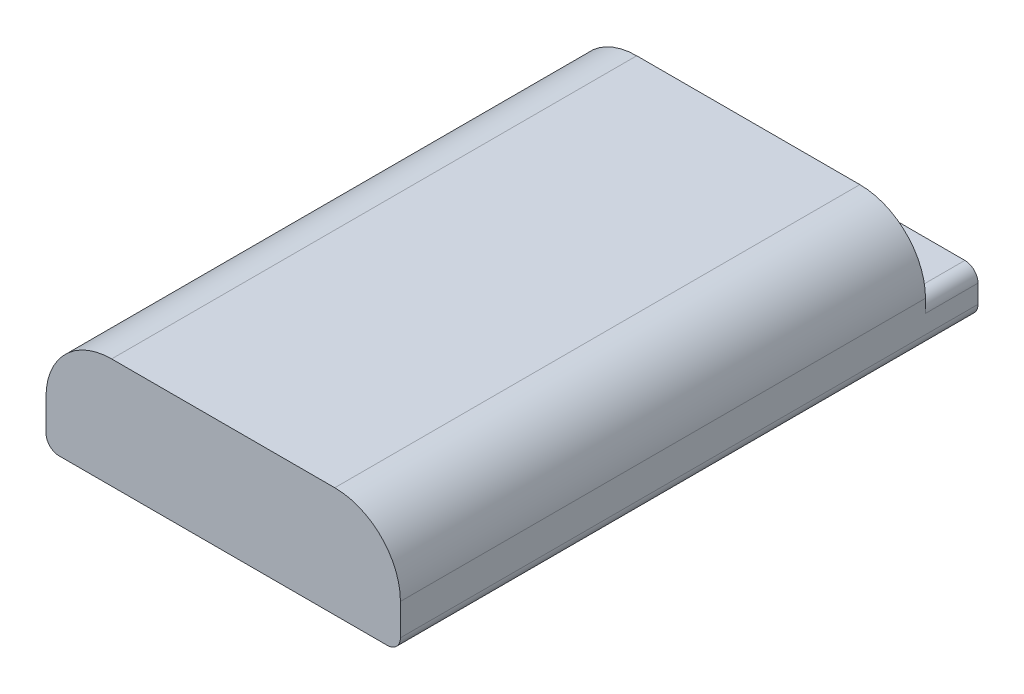
SolidWorks part; units mm, degrees
ref_plane "Front Plane" through (0, 0, 0) normal (0, 0, 1) x (1, 0, 0)
ref_plane "Top Plane" through (0, 0, 0) normal (0, 1, 0) x (1, 0, 0)
ref_plane "Right Plane" through (0, 0, 0) normal (1, 0, 0) x (0, 0, -1)
sketch "Sketch1" plane through (0, 0, 0) normal (0, 1, 0) x (1, 0, 0)
  line L1 (-17.145, 27.94) -> (17.145, 27.94)
  line L2 (-17.145, 27.94) -> (-17.145, -27.94)
  line L3 (-17.145, -27.94) -> (17.145, -27.94)
  line L4 (17.145, 27.94) -> (17.145, -27.94)
  line L5 (-17.145, 27.94) -> (17.145, -27.94) construction
  line L6 (-17.145, -27.94) -> (17.145, 27.94) construction
  point P0 (0, 0)
  dimension "D1" = 55.88
  dimension "D2" = 34.29
extrude "Boss-Extrude1" add sketch "Sketch1" along normal blind 4.318
sketch "Sketch2" plane through (0, 4.318, 0) normal (0, 1, 0) x (1, 0, 0)
  line L0 (17.145, -27.94) -> (17.145, 27.94) construction
  line L1 (-17.145, -27.94) -> (17.145, -27.94)
  line L2 (-17.145, -27.94) -> (-17.145, 22.86)
  line L3 (-17.145, 22.86) -> (17.145, 22.86)
  line L4 (17.145, -27.94) -> (17.145, 22.86)
  dimension "D1" = 50.8
extrude "Boss-Extrude2" add sketch "Sketch2" along normal blind 6.35
sketch "Sketch3" plane through (0, 0, -27.94) normal (0, 0, -1) x (-1, 0, 0)
  line L4 (-17.145, 0) -> (17.145, 0)
  line L5 (17.145, 0) -> (17.145, 4.318)
  line L6 (17.145, 4.318) -> (-17.145, 4.318)
  line L7 (-17.145, 4.318) -> (-17.145, 0)
  line L8 (-15.875, 0) -> (15.875, 0)
  line L9 (17.145, 1.27) -> (17.145, 3.048)
  line L10 (15.875, 4.318) -> (-15.875, 4.318)
  line L11 (-17.145, 3.048) -> (-17.145, 1.27)
  arc A0 (17.145, 3.048) -> (15.875, 4.318) centre (15.875, 3.048) ccw
  arc A1 (15.875, 0) -> (17.145, 1.27) centre (15.875, 1.27) ccw
  arc A2 (-15.875, 0) -> (-17.145, 1.27) centre (-15.875, 1.27) cw
  arc A3 (-15.875, 4.318) -> (-17.145, 3.048) centre (-15.875, 3.048) ccw
  dimension "D2" = 1.27
  dimension "D1" = 0
extrude "Cut-Extrude1" cut sketch "Sketch3" against normal up to surface (5.08 mm away) flip side to cut up to face at (0, 7.493, -22.86)
sketch "Sketch4" plane through (0, 0, -22.86) normal (0, 0, -1) x (-1, 0, 0)
  line L0 (15.875, 0) -> (17.145, 0) construction
  line L1 (17.145, 0) -> (17.145, 1.27) construction
  line L2 (-17.145, 0) -> (-15.875, 0) construction
  line L3 (-17.145, 1.27) -> (-17.145, 0) construction
  line L4 (-17.145, 10.668) -> (-17.145, 3.048) construction
  line L5 (-15.875, 4.318) -> (15.875, 4.318) construction
  line L6 (17.145, 3.048) -> (17.145, 10.668) construction
  line L7 (17.145, 10.668) -> (-17.145, 10.668) construction
  line L8 (15.875, 0) -> (17.145, 0)
  line L9 (17.145, 0) -> (17.145, 1.27)
  line L10 (-17.145, 0) -> (-15.875, 0)
  line L11 (-17.145, 1.27) -> (-17.145, 0)
  line L12 (-17.145, 4.318) -> (-17.145, 3.048)
  line L13 (-15.875, 4.318) -> (15.875, 4.318)
  line L14 (17.145, 3.048) -> (17.145, 4.318)
  line L15 (10.795, 10.668) -> (-10.795, 10.668)
  arc A0 (15.875, 0) -> (17.145, 1.27) centre (15.875, 1.27) ccw construction
  arc A1 (-17.145, 1.27) -> (-15.875, 0) centre (-15.875, 1.27) ccw construction
  arc A2 (-15.875, 4.318) -> (-17.145, 3.048) centre (-15.875, 3.048) ccw construction
  arc A3 (17.145, 3.048) -> (15.875, 4.318) centre (15.875, 3.048) ccw construction
  arc A4 (15.875, 0) -> (17.145, 1.27) centre (15.875, 1.27) ccw
  arc A5 (-17.145, 1.27) -> (-15.875, 0) centre (-15.875, 1.27) ccw
  arc A6 (-15.875, 4.318) -> (-17.145, 3.048) centre (-15.875, 3.048) ccw
  arc A7 (17.145, 3.048) -> (15.875, 4.318) centre (15.875, 3.048) ccw
  arc A8 (17.145, 4.318) -> (10.795, 10.668) centre (10.795, 4.318) ccw
  arc A9 (-17.145, 4.318) -> (-10.795, 10.668) centre (-10.795, 4.318) cw
  line M7 (-17.145, 10.668) -> (-17.145, 3.048)
  line M11 (17.145, 3.048) -> (17.145, 10.668)
  line M12 (17.145, 10.668) -> (-17.145, 10.668)
  dimension "D1" = 6.35
extrude "Cut-Extrude2" cut sketch "Sketch4" against normal through all contours A9 M7 M12 | A8 M11 M12 | L11 L10 A5 | L9 A4 L8
sketch "Sketch6" plane through (0, 4.318, 0) normal (0, 1, 0) x (1, 0, 0)
  line L0 (-15.875, 25.4) -> (15.875, 25.4) construction
  line L1 (-15.875, 22.86) -> (-15.875, 27.94) construction
  line L2 (15.875, 22.86) -> (15.875, 27.94) construction
  line L3 (0, -5.8674) -> (0, 5.8674) construction
  circle A0 centre (-2.54, 25.4) radius 0.635
  circle A1 centre (2.54, 25.4) radius 0.635
  point P8 (0, 25.4)
  dimension "D1" = 1.27
  dimension "D2" = 2.54
extrude "Cut-Extrude3" cut sketch "Sketch6" against normal blind 0.127
